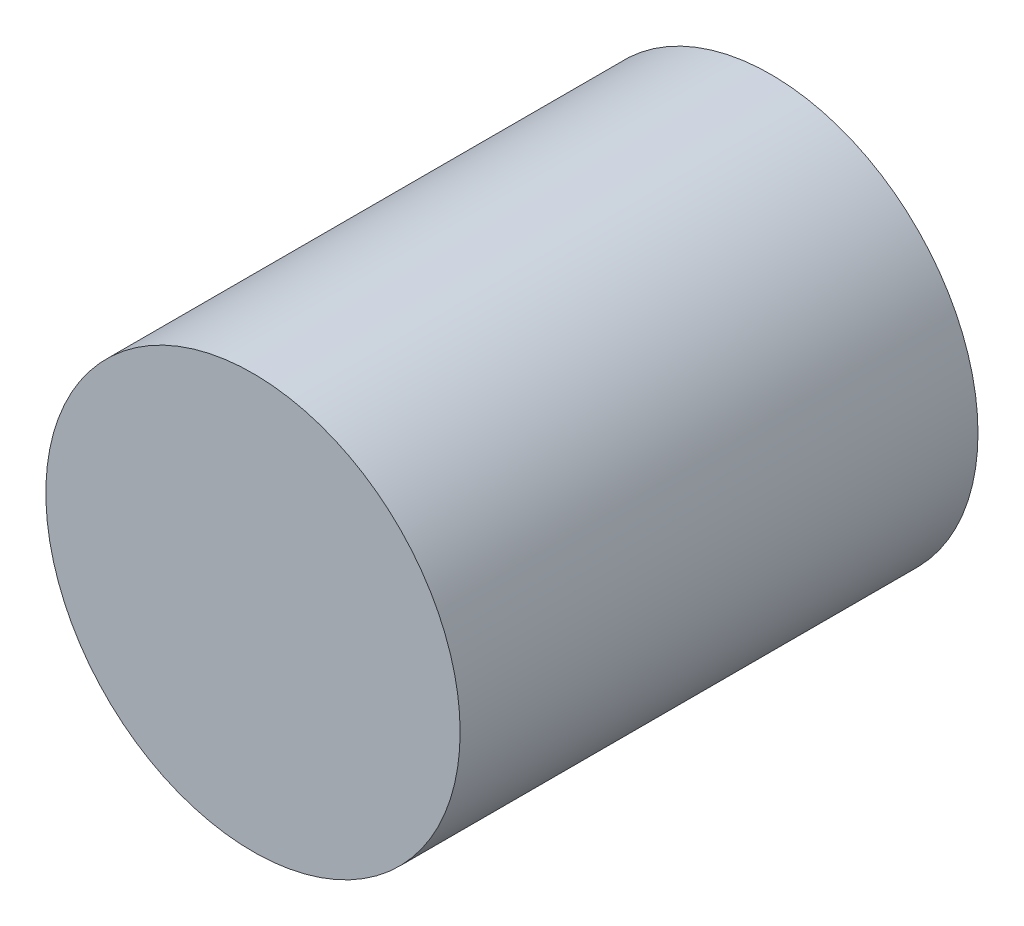
SolidWorks part; units mm, degrees
ref_plane "Front Plane" through (0, 0, 0) normal (0, 0, 1) x (1, 0, 0)
ref_plane "Top Plane" through (0, 0, 0) normal (0, 1, 0) x (1, 0, 0)
ref_plane "Right Plane" through (0, 0, 0) normal (1, 0, 0) x (0, 0, -1)
sketch "Sketch2" plane through (0, 0, 0) normal (0, 0, 1) x (1, 0, 0)
  circle A0 centre (0, 0) radius 20
  dimension "D1" = 40
extrude "Boss-Extrude1" add sketch "Sketch2" along normal blind 50
